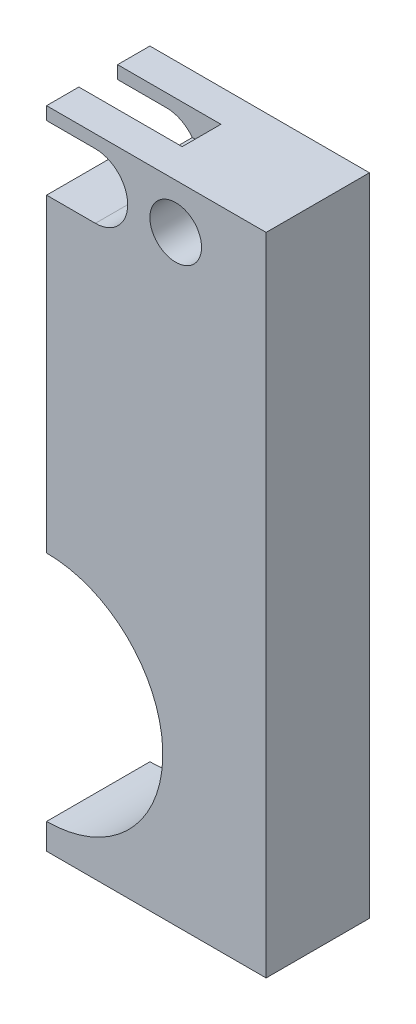
SolidWorks part; units mm, degrees
ref_plane "Front Plane" through (0, 0, 0) normal (0, 0, 1) x (1, 0, 0)
ref_plane "Top Plane" through (0, 0, 0) normal (0, 1, 0) x (1, 0, 0)
ref_plane "Right Plane" through (0, 0, 0) normal (1, 0, 0) x (0, 0, -1)
sketch "Sketch1" plane through (0, 0, 0) normal (0, 0, 1) x (1, 0, 0)
  line L3 (0.688, 7.0084) -> (0.688, -15.9916)
  line L4 (0.688, -33.9916) -> (0.688, -35.9916)
  line L5 (0.688, -35.9916) -> (17.688, -35.9916)
  line L6 (17.688, -35.9916) -> (17.688, 14.0084)
  line L9 (0.688, 14.0084) -> (0.688, 13.0084)
  line L10 (0.688, 13.0084) -> (4.4679, 13.0084)
  line L11 (4.4679, 8.0084) -> (0.688, 8.0084)
  line L12 (0.688, 8.0084) -> (0.688, 7.0084)
  line L14 (0.688, 14.0084) -> (17.688, 14.0084)
  arc A0 (0.688, -15.9916) -> (0.688, -33.9916) centre (0.688, -24.9916) cw
  arc A1 (4.4679, 8.0084) -> (4.4679, 13.0084) centre (4.4679, 10.5084) ccw
  point P0 (0, 0)
  dimension "D2" = 9
  dimension "D4" = 2.5
  dimension "D1" = 50
  dimension "D3" = 2
  dimension "D5" = 1
  dimension "D6" = 1
  dimension "D7" = 17
  dimension "D8" = 23
extrude "Boss-Extrude1" add sketch "Sketch1" along normal blind 8
sketch "Sketch2" plane through (0, 0, 8) normal (0, 0, 1) x (1, 0, 0)
  line L0 (17.688, -35.9916) -> (17.688, 14.0084) construction
  circle A0 centre (10.688, 10.5084) radius 2
  dimension "D1" = 4
  dimension "D2" = 7
extrude "Cut-Extrude1" cut sketch "Sketch2" against normal blind 8
sketch "Sketch3" plane through (0, 14.0084, 0) normal (0, 1, 0) x (1, 0, 0)
  line L0 (0.688, -2.5) -> (8.688, -2.5)
  line L1 (0.688, -8) -> (0.688, 0) construction
  line L2 (8.688, -2.5) -> (8.688, -5.5)
  line L3 (8.688, -5.5) -> (0.688, -5.5)
  line L4 (0.688, -5.5) -> (0.688, -2.5)
  line L5 (17.688, 0) -> (0.688, 0) construction
  point P4 (0.688, -4)
  dimension "D1" = 4
  dimension "D2" = 8
  dimension "D3" = 3
extrude "Cut-Extrude2" cut sketch "Sketch3" against normal blind 2
